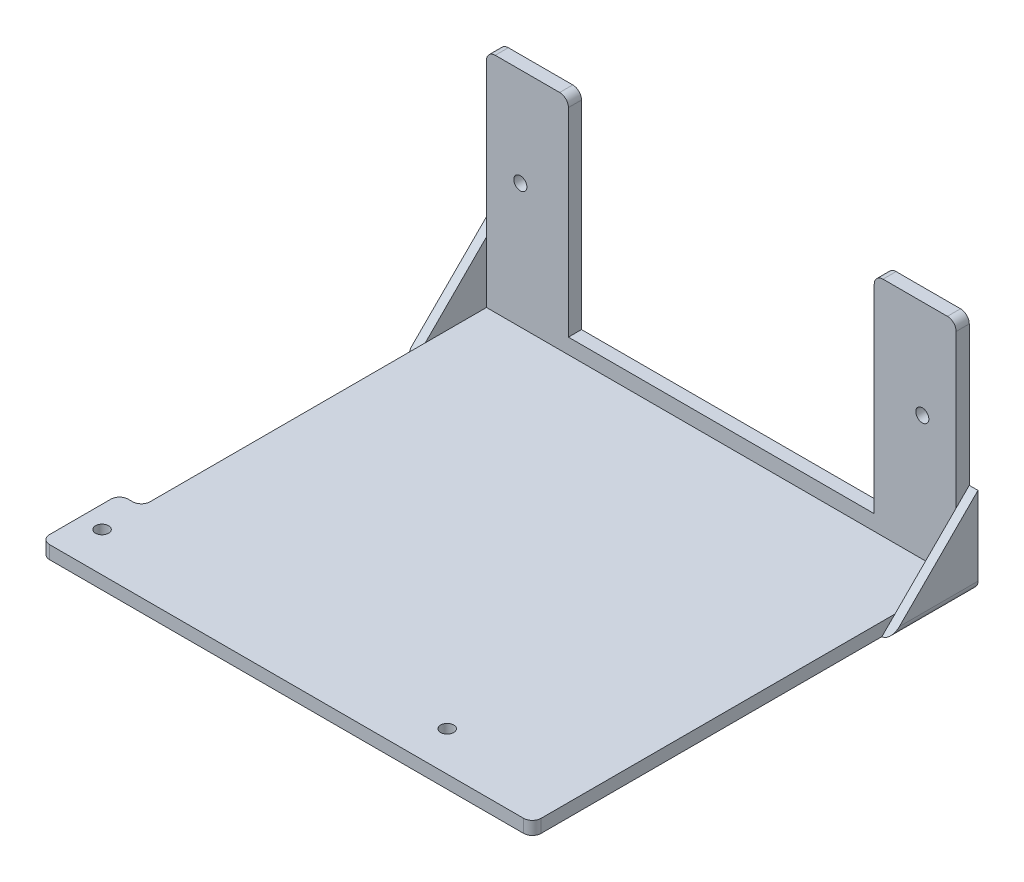
SolidWorks part; units mm, degrees
ref_plane "前视基准面" through (0, 0, 0) normal (0, 0, 1) x (1, 0, 0)
ref_plane "上视基准面" through (0, 0, 0) normal (0, 1, 0) x (1, 0, 0)
ref_plane "右视基准面" through (0, 0, 0) normal (1, 0, 0) x (0, 0, -1)
sketch "草图1" plane through (0, 0, 0) normal (0, 0, 1) x (1, 0, 0)
  line L1 (-53.75, 54) -> (53.75, 54)
  line L2 (-53.75, 54) -> (-53.75, 0)
  line L3 (-53.75, 0) -> (53.75, 0)
  line L4 (53.75, 54) -> (53.75, 0)
  dimension "D1" = 107.5
  dimension "D2" = 54
  dimension "D3" = 53.75
extrude "凸台-拉伸1" add sketch "草图1" along normal blind 3
sketch "草图2" plane through (0, 0, 3) normal (0, 0, 1) x (1, 0, 0)
  line L0 (-53.75, 54) -> (-53.75, 0) construction
  line L1 (53.75, 0) -> (-53.75, 0)
  line L2 (53.75, 0) -> (53.75, 3)
  line L3 (53.75, 3) -> (-53.75, 3)
  line L4 (-53.75, 0) -> (-53.75, 3)
  dimension "D1" = 3
extrude "凸台-拉伸2" add sketch "草图2" along normal blind 97
sketch "草图4" plane through (0, 3, 0) normal (0, 1, 0) x (1, 0, 0)
  line L1 (-53.75, -100) -> (-58.75, -100)
  line L2 (-53.75, -100) -> (-53.75, -82)
  line L3 (-53.75, -82) -> (-58.75, -82)
  line L4 (-58.75, -100) -> (-58.75, -82)
  dimension "D1" = 18
  dimension "D2" = 5
extrude "凸台-拉伸3" add sketch "草图4" against normal blind 3
sketch "草图5" plane through (0, 3, 0) normal (0, 1, 0) x (1, 0, 0)
  line L0 (53.75, -100) -> (-58.75, -100) construction
  line L1 (-53.75, -3) -> (-53.75, 0) construction
  circle A0 centre (-53.75, -91) radius 1.5
  circle A1 centre (25.25, -91) radius 1.5
  dimension "D1" = 3
  dimension "D2" = 79
  dimension "D3" = 9
  dimension "D4" = 9
extrude "切除-拉伸1" cut sketch "草图5" against normal blind 3
sketch "草图6" plane through (0, 0, 3) normal (0, 0, 1) x (1, 0, 0)
  line L0 (53.75, 54) -> (-53.75, 54) construction
  line L1 (-35, 54) -> (35, 54)
  line L2 (-35, 54) -> (-35, 6.5)
  line L3 (-35, 6.5) -> (35, 6.5)
  line L4 (35, 54) -> (35, 6.5)
  line L5 (53.75, 3) -> (53.75, 54) construction
  dimension "D1" = 70
  dimension "D2" = 47.5
  dimension "D3" = 18.75
extrude "切除-拉伸2" cut sketch "草图6" against normal blind 3
sketch "草图7" plane through (0, 0, 3) normal (0, 0, 1) x (1, 0, 0)
  line L0 (35, 6.5) -> (35, 54) construction
  line L1 (53.75, 54) -> (35, 54) construction
  line L2 (-35, 54) -> (-53.75, 54) construction
  line L3 (-35, 54) -> (-35, 6.5) construction
  circle A0 centre (46, 31.5) radius 1.5
  circle A1 centre (-46, 31.5) radius 1.5
  dimension "D1" = 3
  dimension "D4" = 22.5
  dimension "D6" = 3
  dimension "D2" = 11
  dimension "D3" = 22.5
  dimension "D5" = 11
extrude "切除-拉伸3" cut sketch "草图7" against normal blind 3
sketch "草图8" plane through (-53.75, 0, 0) normal (-1, 0, 0) x (0, 0, 1)
  line L0 (0, 0) -> (20, 0)
  line L1 (82, 0) -> (0, 0) construction
  line L2 (20, 0) -> (0, 20)
  line L3 (0, 54) -> (0, 0) construction
  line L4 (0, 20) -> (0, 0)
  dimension "D1" = 20
  dimension "D2" = 20
extrude "凸台-拉伸4" add sketch "草图8" along normal blind 2
sketch "草图9" plane through (53.75, 0, 0) normal (1, 0, 0) x (0, 0, -1)
  line L0 (0, 0) -> (0, 20)
  line L1 (0, 20) -> (-20, 0)
  line L2 (-100, 0) -> (0, 0) construction
  line L3 (-20, 0) -> (0, 0)
  dimension "D1" = 20
extrude "凸台-拉伸5" add sketch "草图9" along normal blind 2
fillet "圆角1" radius 2 6 edges at (-55.75, 0, 10) (55.75, 0, 10) (53.75, 54, 1.5) (35, 54, 1.5) (-35, 54, 1.5) (-53.75, 54, 1.5)
fillet "圆角2" radius 2 4 edges at (53.75, 1.5, 100) (-58.75, 1.5, 100) (-58.75, 1.5, 82) (-53.75, 1.5, 82)
